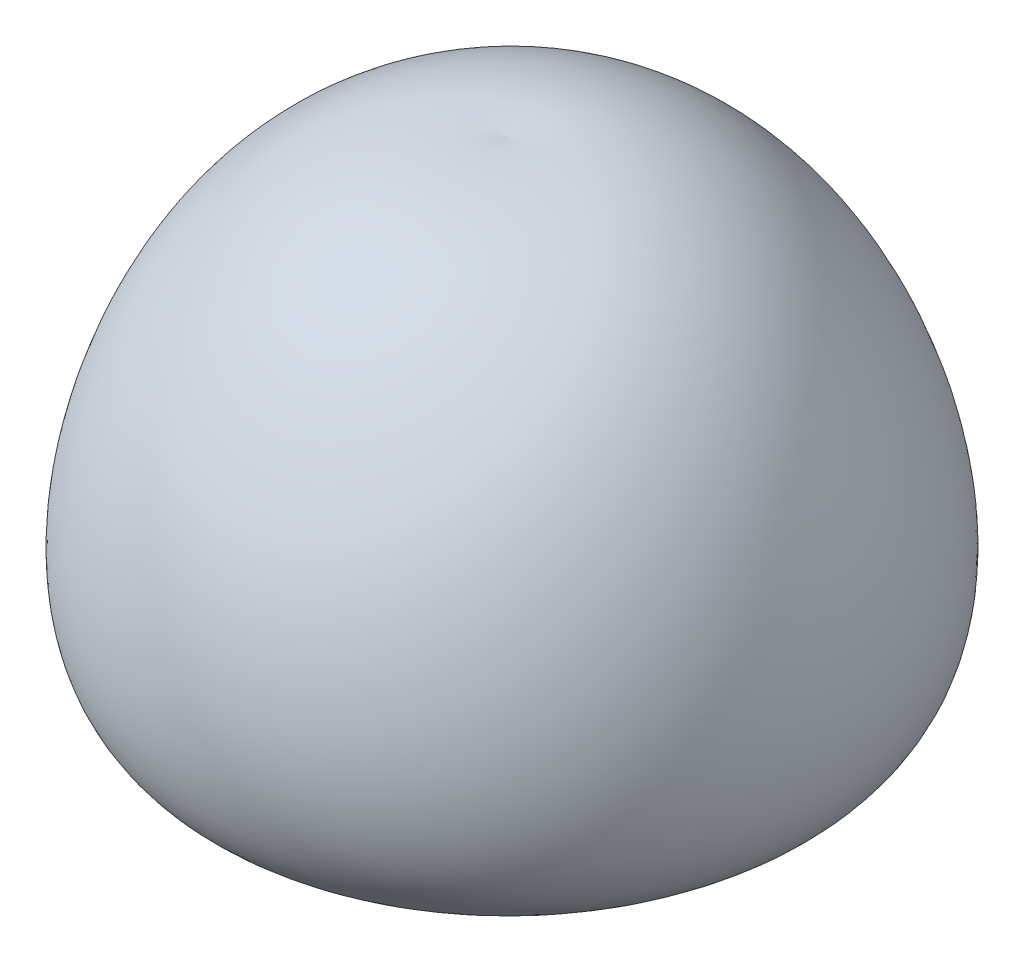
SolidWorks part; units mm, degrees
ref_plane "前视基准面" through (0, 0, 0) normal (0, 0, 1) x (1, 0, 0)
ref_plane "上视基准面" through (0, 0, 0) normal (0, 1, 0) x (1, 0, 0)
ref_plane "右视基准面" through (0, 0, 0) normal (1, 0, 0) x (0, 0, -1)
sketch "草图1" plane through (0, 0, 0) normal (0, 0, 1) x (1, 0, 0)
  line L0 (2.3163, 8.0774) -> (2.4735, -1.9226)
  spline S0 degree 3 poles (2.3163, 8.0774) (-0.8457, 8.4306) (-6.7082, 3.2355) (-5.436, -6.4685) (2.4735, -1.9226) knots 0 0 0 0 0.408525 1 1 1 1
  point P1 (-2.4365, 15.8855)
  point P2 (-8.8166, -0.387)
  point P6 (-9.155, 9.5376)
  point P8 (-3.9516, 17.0508)
  point P9 (-2.3345, 4.8111)
  point P10 (-4.4449, 3.4335)
  point P11 (-5.0363, -1.575)
  point P12 (-0.9704, 7.483)
  dimension "D1" = 10
revolve "旋转1" add sketch "草图1" angle 360 about L0
